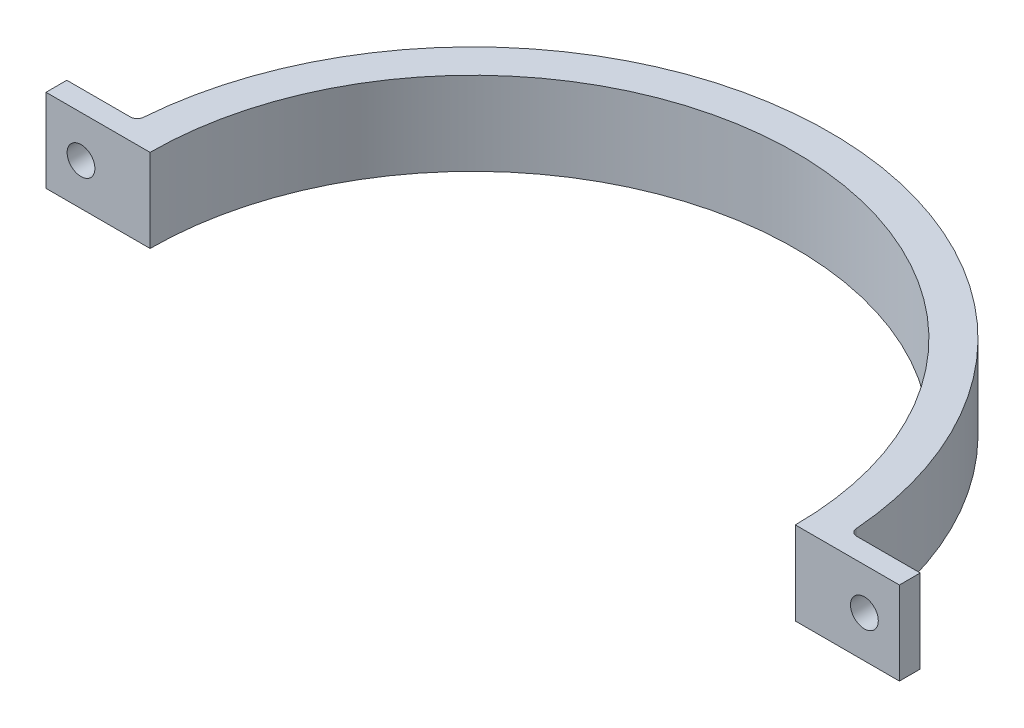
SolidWorks part; units mm, degrees
ref_plane "Front Plane" through (0, 0, 0) normal (0, 0, 1) x (1, 0, 0)
ref_plane "Top Plane" through (0, 0, 0) normal (0, 1, 0) x (1, 0, 0)
ref_plane "Right Plane" through (0, 0, 0) normal (1, 0, 0) x (0, 0, -1)
sketch "Sketch1" plane through (0, 0, 0) normal (0, 1, 0) x (1, 0, 0)
  line L0 (-51.5, 0) -> (-46.5, 0) construction
  line L1 (-46.5, 0) -> (46.5, 0) construction
  line L2 (46.5, 0) -> (51.5, 0) construction
  line L3 (51.5, 0) -> (61.5, 0) construction
  line L4 (61.5, -3) -> (61.5, 3)
  line L5 (61.5, 3) -> (51.4125, 3)
  line L6 (61.5, -3) -> (51.4125, -3)
  line L7 (0, -6.6) -> (0, 6.6) construction
  line L8 (-51.5, 0) -> (-61.5, 0) construction
  line L9 (-61.5, 3) -> (-51.4125, 3)
  line L10 (-61.5, -3) -> (-61.5, 3)
  line L11 (-61.5, -3) -> (-51.4125, -3)
  circle A0 centre (0, 0) radius 46.5
  arc A1 (51.4125, 3) -> (-51.4125, 3) centre (0, 0) ccw
  arc A2 (51.5, 0) -> (51.4125, 3) centre (0, 0) ccw construction
  circle A3 centre (0, 0) radius 51.5 construction
  arc A4 (51.4125, -3) -> (51.5, 0) centre (0, 0) ccw construction
  arc A5 (-51.4125, 3) -> (-51.5, 0) centre (0, 0) ccw construction
  arc A6 (-51.4125, -3) -> (51.4125, -3) centre (0, 0) ccw
  arc A7 (-51.5, 0) -> (-51.4125, -3) centre (0, 0) ccw construction
  point P8 (0, 0)
  point P14 (61.5, 0)
  dimension "D1" = 93
  dimension "D3" = 6
  dimension "D4" = 10
  dimension "D2" = 5
extrude "Boss-Extrude1" add sketch "Sketch1" along normal blind 12
sketch "Sketch2" plane through (0, 0, 3) normal (0, 0, 1) x (1, 0, 0)
  line L0 (-61.5, 6) -> (-51.4125, 6) construction
  line L1 (-61.5, 12) -> (-61.5, 0) construction
  line L2 (-51.4125, 12) -> (-51.4125, 0) construction
  line L3 (51.4125, 6) -> (61.5, 6) construction
  line L4 (51.4125, 12) -> (51.4125, 0) construction
  line L5 (61.5, 12) -> (61.5, 0) construction
  circle A0 centre (56.4563, 6) radius 2
  circle A1 centre (-56.4563, 6) radius 2
  dimension "D1" = 4
  dimension "D2" = 4
extrude "Cut-Extrude1" cut sketch "Sketch2" against normal blind 12
split "Split1" trim tools "Front Plane" bodies to split 102 resulting bodies 103 104
sketch "Sketch3" plane through (0, 12, 0) normal (0, 1, 0) x (1, 0, 0)
  line L0 (-47.5, -51.5) -> (47.5, -51.5)
  line L1 (-47.5, -51.5) -> (-47.5, -46.5)
  line L2 (-47.5, -46.5) -> (47.5, -46.5)
  line L3 (47.5, -46.5) -> (47.5, -51.5)
  arc A1 (-51.4125, -3) -> (51.4125, -3) centre (0, 0) ccw construction
  arc A2 (-46.5, 0) -> (46.5, 0) centre (0, 0) ccw construction
  point P0 (0, -46.5)
  point P3 (0, -51.5)
  point P9 (0, -46.5)
  dimension "D1" = 95
extrude "Boss-Extrude2" add sketch "Sketch3" against normal blind 12
other "Move Face1" face at (0, 6, 51.5) parameters "D1"=3
other "Move Face2" face at (34.818, 6, 46.5) face at (-34.818, 6, 46.5) parameters "D1"=3
sketch "Sketch4" plane through (0, 0, 43.5) normal (0, 0, -1) x (-1, 0, 0)
  line L0 (47.5, 6) -> (44.5, 6) construction
  line L1 (47.5, 0) -> (47.5, 12) construction
  circle A0 centre (44.5, 6) radius 2
  dimension "D2" = 4
  dimension "D1" = 3
extrude "Cut-Extrude2" cut sketch "Sketch4" against normal through all
sketch "Sketch5" plane through (0, 0, 43.5) normal (0, 0, -1) x (-1, 0, 0)
  line L1 (47.5, 12) -> (42.6946, 9.5694)
  line L2 (47.5, 0) -> (47.5, 12)
  line L3 (47.5, 0) -> (47.5, 12)
  line L4 (47.5, 0) -> (42.6946, 2.4306)
  arc A1 (42.6946, 2.4306) -> (42.6946, 9.5694) centre (44.5, 6) ccw construction
  circle A2 centre (44.5, 6) radius 4
  arc A3 (42.6946, 9.5694) -> (42.6946, 2.4306) centre (44.5, 6) ccw
  dimension "D1" = 2
  dimension "D2" = 0
extrude "Cut-Extrude3" cut sketch "Sketch5" against normal blind 2
mirror "Mirror1" about plane through (0, 0, 0) normal (1, 0, 0) of "Cut-Extrude3", "Cut-Extrude2"
fillet "Fillet1" radius 1 8 edges at (47.5, 0, 44.5) (47.5, 12, 44.5) (51.4125, 6, 3) (-51.4125, 6, 3) (27.5681, 6, 43.5) (-47.5, 0, 44.5) (-27.5681, 6, 43.5) (-47.5, 12, 44.5)
fillet "Fillet2" radius 1 2 edges at (-51.4125, 6, -3) (51.4125, 6, -3)
delete or keep bodies "Body-Delete/Keep 1" type delete bodies bodies 108
